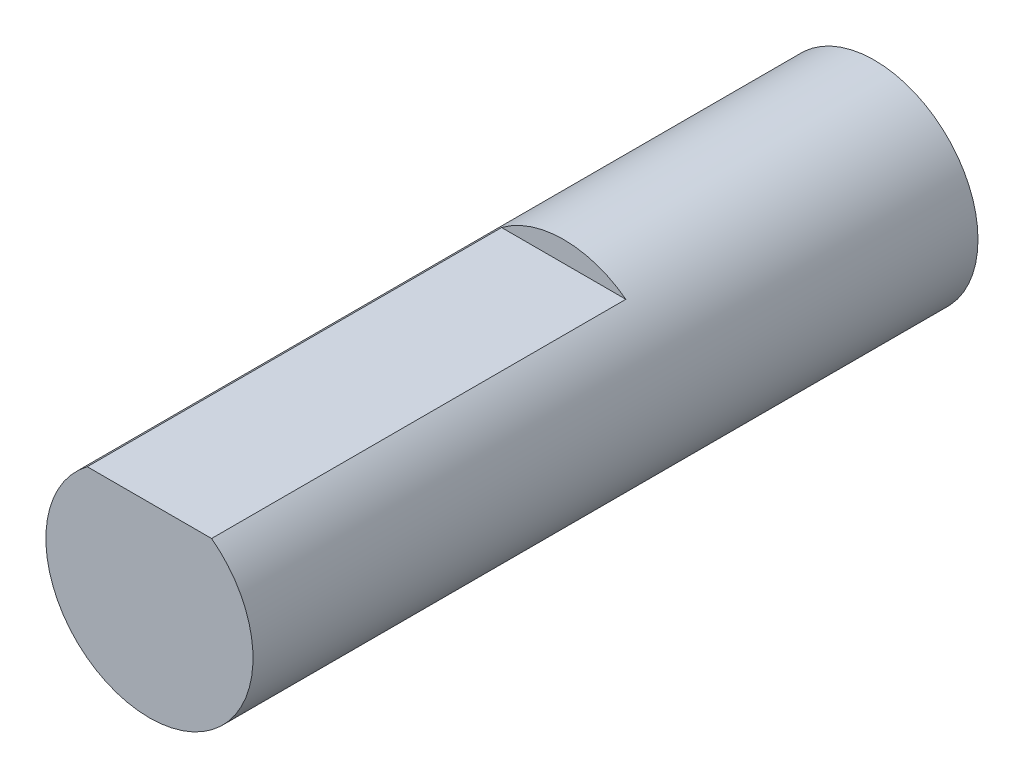
SolidWorks part; units mm, degrees
material "1060 Alloy"
ref_plane "Alzado" through (0, 0, 0) normal (0, 0, 1) x (1, 0, 0)
ref_plane "Planta" through (0, 0, 0) normal (0, 1, 0) x (1, 0, 0)
ref_plane "Vista lateral" through (0, 0, 0) normal (1, 0, 0) x (0, 0, -1)
sketch "Sketch1" plane through (0, 0, 0) normal (0, 0, 1) x (1, 0, 0)
  circle A0 centre (0, 0) radius 2
  dimension "D1" = 4
extrude "Boss-Extrude1" add sketch "Sketch1" along normal blind 14
sketch "Sketch2" plane through (0, 0, 14) normal (0, 0, 1) x (1, 0, 0)
  line L0 (-1.2, 1.6) -> (1.2, 1.6)
  line L1 (0, 1.6) -> (0, -2) construction
  circle A0 centre (0, 0) radius 2 construction
  arc A1 (-1.2, 1.6) -> (1.2, 1.6) centre (0, 0) cw
  dimension "D1" = 3.6
extrude "Cut-Extrude1" cut sketch "Sketch2" against normal blind 8
